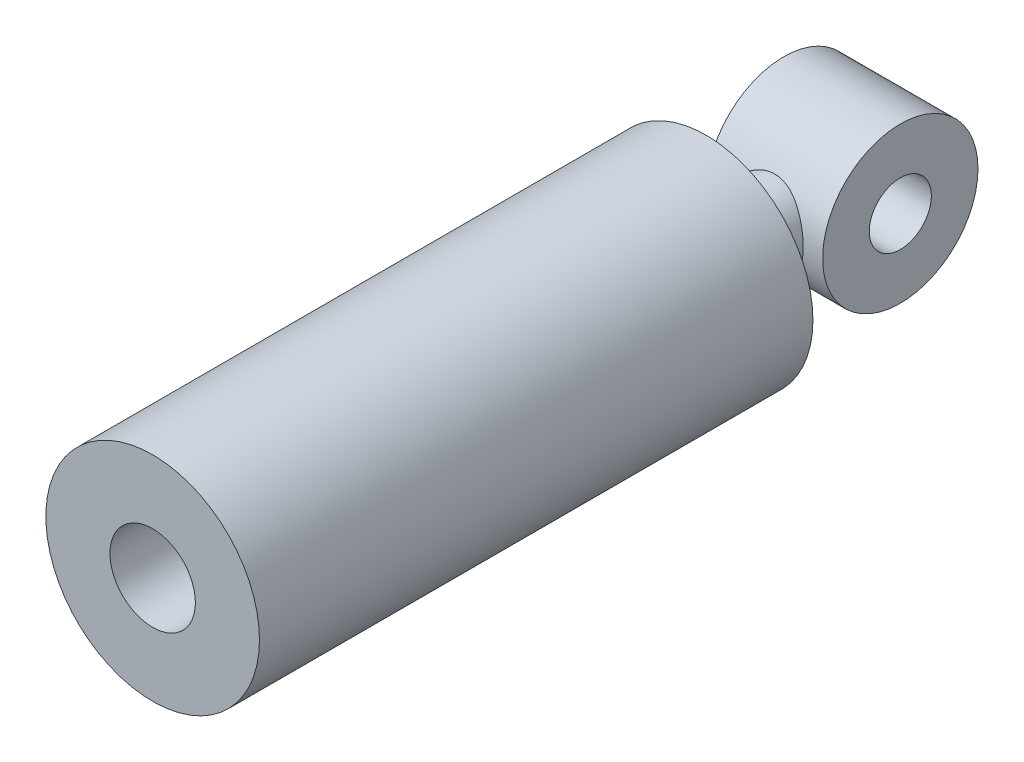
SolidWorks part; units mm, degrees
ref_plane "Front Plane" through (0, 0, 0) normal (0, 0, 1) x (1, 0, 0)
ref_plane "Top Plane" through (0, 0, 0) normal (0, 1, 0) x (1, 0, 0)
ref_plane "Right Plane" through (0, 0, 0) normal (1, 0, 0) x (0, 0, -1)
sketch "Cylinder Section" plane through (0, 0, 0) normal (0, 1, 0) x (1, 0, 0)
  line L0 (0, -3) -> (2, -3)
  line L1 (2, -3) -> (2, -7)
  line L2 (2, -7) -> (5.5, -7)
  line L3 (5.5, -7) -> (5.5, -35.5)
  line L4 (5.5, -35.5) -> (2.2, -35.5)
  line L5 (2.2, -35.5) -> (2.2, -12)
  line L6 (2.2, -12) -> (0, -12)
  line L7 (0, -12) -> (0, -3)
  line L8 (0, -10.123) -> (0, 10.123) construction
  dimension "D1" = 2
  dimension "D2" = 5.5
  dimension "D3" = 2.2
  dimension "D4" = 3
  dimension "D5" = 7
  dimension "D6" = 35.5
  dimension "D7" = 12
  dimension "D8" = 10.123
  dimension "D9" = 10.123
revolve "Cylinder Revolve" add sketch "Cylinder Section" angle 360 about L8
sketch "Eye Sketch" plane through (0, 0, 0) normal (1, 0, 0) x (0, 0, -1)
  circle A0 centre (0, 0) radius 4
  dimension "D1" = 8
extrude "Eye Extrude" add sketch "Eye Sketch" along normal mid plane 6
sketch "Eye Bore Sketch" plane through (0, 0, 0) normal (1, 0, 0) x (0, 0, -1)
  circle A0 centre (0, 0) radius 1.6
  dimension "D1" = 3.2
extrude "Eye Bore Cut" cut sketch "Eye Bore Sketch" against normal mid plane 6
equation "\"eye_diameter\"= 8mm 'Mock shock eye outside diameter"
equation "\"eye_width\"= 6mm 'Eye width along hinge axis X"
equation "\"eye_bore\"= 3.2mm 'M3 hinge clearance"
equation "\"rod_diameter\"= 4mm 'Sliding rod diameter"
equation "\"neck_start\"= 3mm 'Neck junction inside eye"
equation "\"cylinder_diameter\"= 11mm 'Mock shock cylinder outside diameter"
equation "\"cylinder_start\"= 7mm 'Cylinder lower shoulder"
equation "\"cylinder_end\"= 35.5mm 'Cylinder open end"
equation "\"bore_start\"= 12mm 'Bottom of sliding bore"
equation "\"bore_diameter\"= 4.4mm 'Sliding bore diameter"
equation "\"axis_reference_halfspan\"= 10.123mm 'Half display length of the construction axis; avoids sharing a profile endpoint"
equation "\"D1@Cylinder Section\"= \"rod_diameter\" / 2"
equation "\"D2@Cylinder Section\"= \"cylinder_diameter\" / 2"
equation "\"D3@Cylinder Section\"= \"bore_diameter\" / 2"
equation "\"D4@Cylinder Section\"= \"neck_start\""
equation "\"D5@Cylinder Section\"= \"cylinder_start\""
equation "\"D6@Cylinder Section\"= \"cylinder_end\""
equation "\"D7@Cylinder Section\"= \"bore_start\""
equation "\"D8@Cylinder Section\"= \"axis_reference_halfspan\""
equation "\"D9@Cylinder Section\"= \"axis_reference_halfspan\""
equation "\"full_turn\"= 360deg 'Full circular extent for revolves and patterns"
equation "\"D1@Cylinder Revolve\"= \"full_turn\""
equation "\"D1@Eye Sketch\"= \"eye_diameter\""
equation "\"D1@Eye Extrude\"= \"eye_width\""
equation "\"D1@Eye Bore Sketch\"= \"eye_bore\""
equation "\"D1@Eye Bore Cut\"= \"eye_width\""
